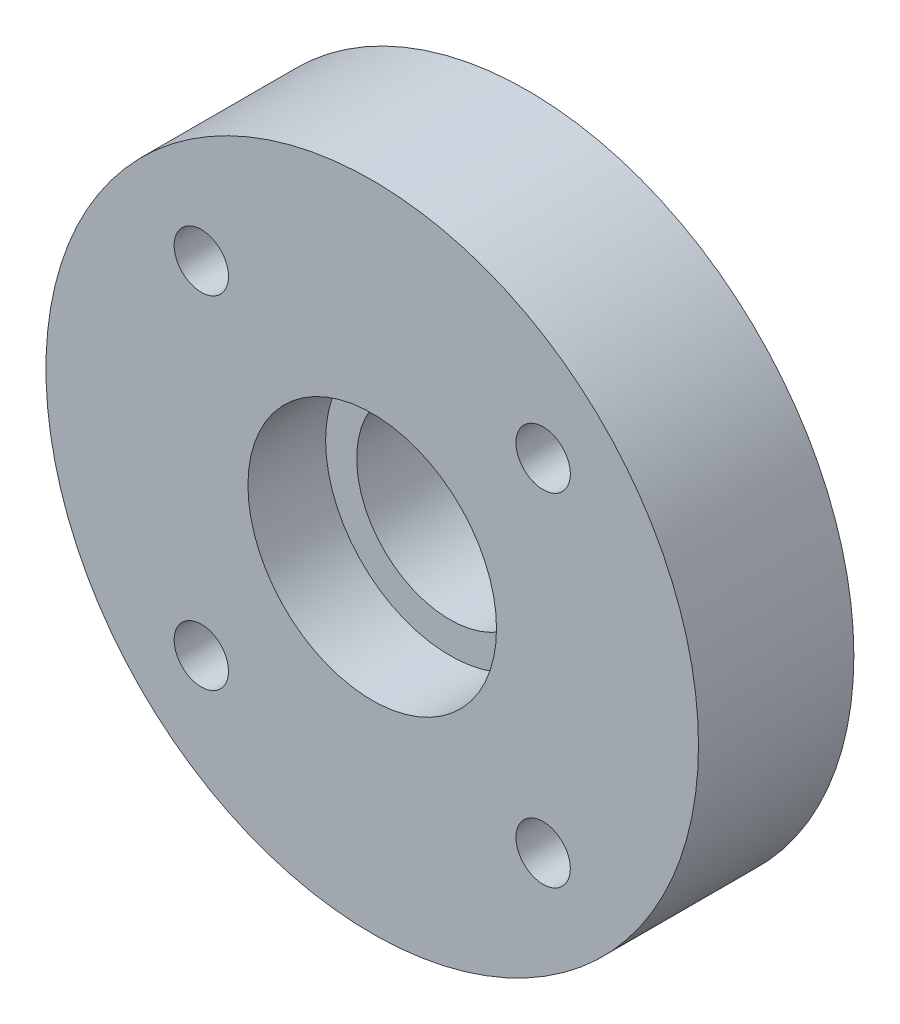
SolidWorks part; units mm, degrees
ref_plane "Front Plane" through (0, 0, 0) normal (0, 0, 1) x (1, 0, 0)
ref_plane "Top Plane" through (0, 0, 0) normal (0, 1, 0) x (1, 0, 0)
ref_plane "Right Plane" through (0, 0, 0) normal (1, 0, 0) x (0, 0, -1)
sketch "Sketch1" plane through (0, 0, 0) normal (0, 0, 1) x (1, 0, 0)
  circle A0 centre (0, 0) radius 21
  dimension "D1" = 42
extrude "Boss-Extrude1" add sketch "Sketch1" along normal blind 10
sketch "Sketch2" plane through (0, 0, 10) normal (0, 0, 1) x (1, 0, 0)
  circle A0 centre (0, 0) radius 6
  dimension "D1" = 12
extrude "Cut-Extrude1" cut sketch "Sketch2" against normal through all contours A0
sketch "Sketch3" plane through (0, 0, 10) normal (0, 0, 1) x (1, 0, 0)
  circle A0 centre (0, 0) radius 8
  dimension "D1" = 16
extrude "Cut-Extrude2" cut sketch "Sketch3" against normal blind 5
sketch "Sketch4" plane through (0, 0, 10) normal (0, 0, 1) x (1, 0, 0)
  line L0 (3.3425, 0) -> (0, 0) construction
  line L1 (0, 0) -> (0, 4.812) construction
  circle A0 centre (-11, 11) radius 1.75
  circle A1 centre (11, 11) radius 1.75
  circle A2 centre (11, -11) radius 1.75
  circle A3 centre (-11, -11) radius 1.75
  dimension "D1" = 3.5
  dimension "D2" = 11
  dimension "D3" = 11
extrude "Cut-Extrude3" cut sketch "Sketch4" against normal through all
